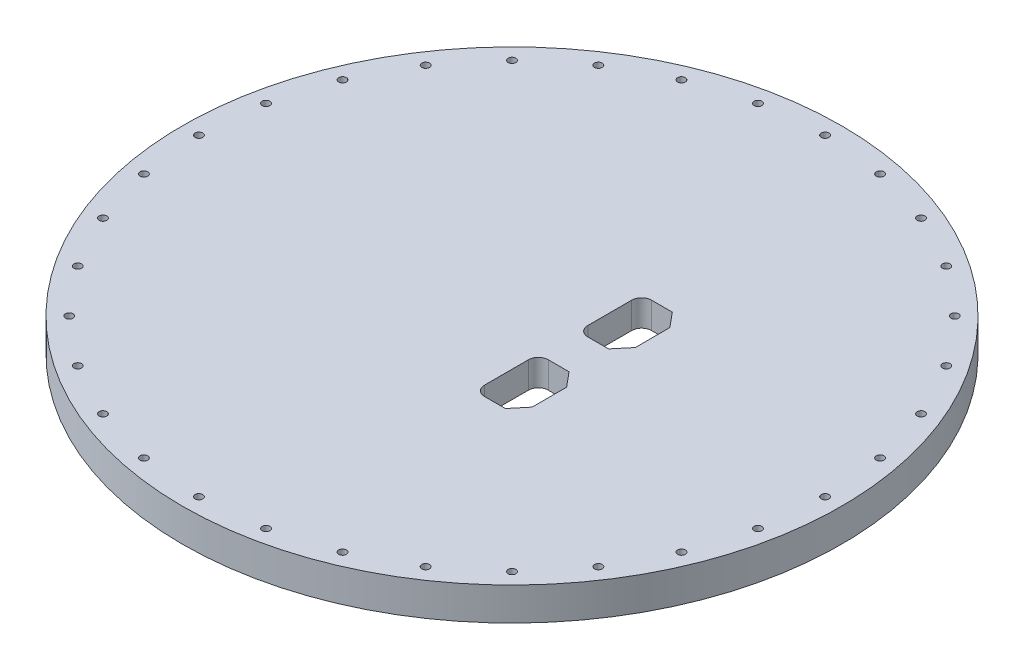
SolidWorks part; units mm, degrees
ref_plane "Front Plane" through (0, 0, 0) normal (0, 0, 1) x (1, 0, 0)
ref_plane "Top Plane" through (0, 0, 0) normal (0, 1, 0) x (1, 0, 0)
ref_plane "Right Plane" through (0, 0, 0) normal (1, 0, 0) x (0, 0, -1)
sketch "Sketch2" plane through (0, 0, 0) normal (0, 0, 1) x (1, 0, 0)
  line L0 (0, 0) -> (13.5, 0) construction
  line L1 (0, 0) -> (0, 12) construction
  line L2 (13.5, 0) -> (13.5, 0.3)
  line L3 (13.5, 0.3) -> (0, 0.3)
  line L4 (0, 0.3) -> (0, 1.5)
  line L5 (0, 1.5) -> (15, 1.5)
  line L6 (15, 1.5) -> (15, 0)
  line L7 (15, 0) -> (13.5, 0)
  dimension "D1" = 13.5
  dimension "D2" = 12
  dimension "D3" = 1.2
  dimension "D4" = 1.5
  dimension "D5" = 0.3
revolve "Revolve1" add sketch "Sketch2" angle 360 about L1
sketch "Sketch3" plane through (0, 1.5, 0) normal (0, 1, 0) x (1, 0, 0)
  line L0 (3, 2.5168) -> (3, -8.1499) construction
  line L1 (-1.2013, 0) -> (3.7987, 0) construction
  line L2 (2.2, -3.35) -> (2.2, -1.35)
  line L3 (2.55, -1) -> (3.45, -1)
  line L4 (3.45, -1) -> (3.95, -1.6)
  line L5 (3.95, -1.6) -> (3.95, -3.1)
  line L6 (3.95, -3.1) -> (3.45, -3.7)
  line L7 (3.45, -3.7) -> (2.55, -3.7)
  line L8 (3.45, 3.7) -> (2.55, 3.7)
  line L9 (3.95, 3.1) -> (3.45, 3.7)
  line L10 (3.95, 1.6) -> (3.95, 3.1)
  line L11 (3.45, 1) -> (3.95, 1.6)
  line L12 (2.55, 1) -> (3.45, 1)
  line L13 (2.2, 3.35) -> (2.2, 1.35)
  line L14 (2.1, -3.35) -> (2.1, -1.35)
  line L15 (2.55, -0.9) -> (3.4968, -0.9)
  line L16 (3.4968, -0.9) -> (4.05, -1.5638)
  line L17 (4.05, -1.5638) -> (4.05, -3.1362)
  line L18 (4.05, -3.1362) -> (3.4968, -3.8)
  line L19 (3.4968, -3.8) -> (2.55, -3.8)
  line L20 (3.4968, 3.8) -> (2.55, 3.8)
  line L21 (2.1, 3.35) -> (2.1, 1.35)
  line L22 (2.55, 0.9) -> (3.4968, 0.9)
  line L23 (3.4968, 0.9) -> (4.05, 1.5638)
  line L24 (4.05, 1.5638) -> (4.05, 3.1362)
  line L25 (4.05, 3.1362) -> (3.4968, 3.8)
  arc A0 (2.2, -1.35) -> (2.55, -1) centre (2.55, -1.35) cw
  arc A1 (2.55, -3.7) -> (2.2, -3.35) centre (2.55, -3.35) cw
  arc A2 (2.2, 1.35) -> (2.55, 1) centre (2.55, 1.35) ccw
  arc A3 (2.55, 3.7) -> (2.2, 3.35) centre (2.55, 3.35) ccw
  arc A4 (2.1, -1.35) -> (2.55, -0.9) centre (2.55, -1.35) cw
  arc A5 (2.55, -3.8) -> (2.1, -3.35) centre (2.55, -3.35) cw
  arc A6 (2.55, 3.8) -> (2.1, 3.35) centre (2.55, 3.35) ccw
  arc A7 (2.1, 1.35) -> (2.55, 0.9) centre (2.55, 1.35) ccw
  point P14 (3, -1)
  dimension "D2" = 0.35
  dimension "D1" = 2
  dimension "D3" = 0.5
  dimension "D4" = 1.5
  dimension "D5" = 1
  dimension "D6" = 1.75
  dimension "D7" = 0.9
  dimension "D8" = 3
  dimension "D9" = 0.1
  dimension "D10" = 0.1
extrude "Cut-Extrude2" cut sketch "Sketch3" against normal up to surface (1.2 mm away) contours A4 L15 L16 L17 L18 L19 A5 L14 | L21 A7 L22 L23 L24 L25 L20 A6 up to face at (0, 0.3, -13.5)
sketch "Sketch4" plane through (0, 1.5, 0) normal (0, 1, 0) x (1, 0, 0)
  line L0 (0, 0) -> (15, 0) construction
  circle A0 centre (0, 0) radius 15 construction
  circle A1 centre (14.25, 0) radius 0.175
  dimension "D1" = 0.35
  dimension "D2" = 14.25
extrude "Cut-Extrude3" cut sketch "Sketch4" against normal up to surface (1.5 mm away) up to face at (0, 0, -15)
pattern_circular "CirPattern1" count 32 over 360 about axis through (0, 0, 0) along (0, 1, 0) of "Cut-Extrude3"
scale "Scale1" scale about centroid uniform scaling yes scale factor 5
